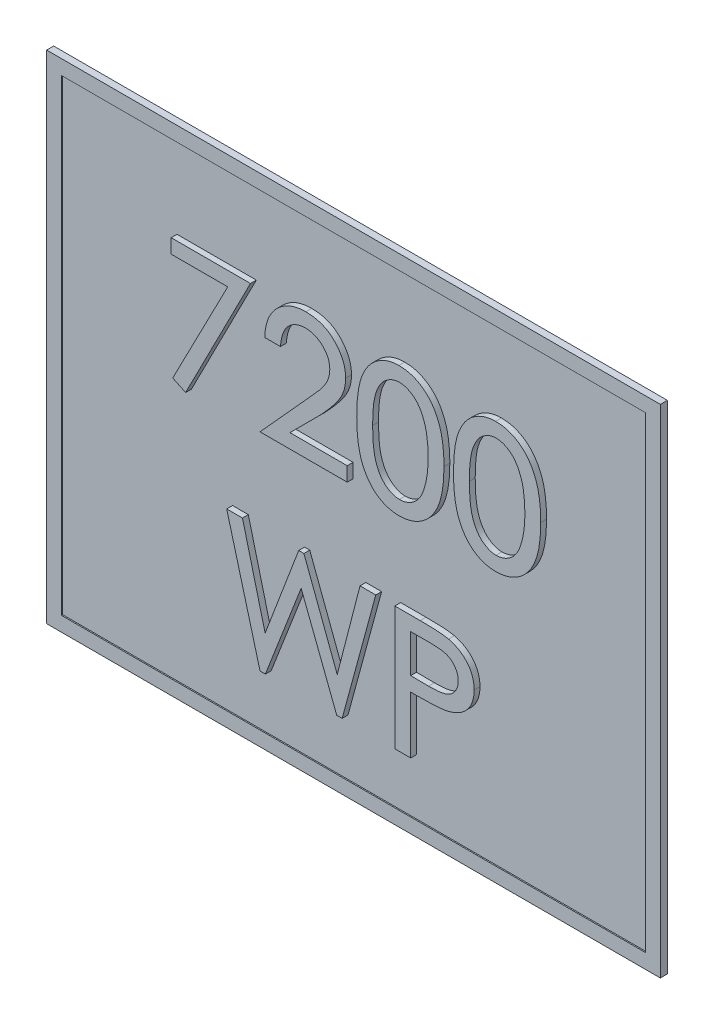
SolidWorks part; units mm, degrees
ref_plane "Front Plane" through (0, 0, 0) normal (0, 0, 1) x (1, 0, 0)
ref_plane "Top Plane" through (0, 0, 0) normal (0, 1, 0) x (1, 0, 0)
ref_plane "Right Plane" through (0, 0, 0) normal (1, 0, 0) x (0, 0, -1)
sketch "Sketch1" plane through (0, 0, 0) normal (0, 0, 1) x (1, 0, 0)
  line L0 (-500, 0) -> (500, 0) construction
  line L1 (-500, 400) -> (500, 400)
  line L2 (-500, 400) -> (-500, -400)
  line L3 (-500, -400) -> (500, -400)
  line L4 (500, 400) -> (500, -400)
  line L5 (-500, 400) -> (500, -400) construction
  line L6 (-500, -400) -> (500, 400) construction
  point P0 (0, 0)
  dimension "D1" = 1000
  dimension "D2" = 800
extrude "Boss-Extrude1" add sketch "Sketch1" along normal blind 10
sketch "Sketch2" plane through (0, 0, 10) normal (0, 0, 1) x (1, 0, 0)
  line L0 (-500, 49.8298) -> (500, 49.8298) construction
  line L3 (-500, 400) -> (-500, -400) construction
  line L4 (500, -400) -> (500, 400) construction
  line L5 (-500, -304.5438) -> (500, -304.5438) construction
  text T0 "<b>7200</b>" font "Century Gothic" height in points 800
  text T1 "<b>WP</b>" font "Century Gothic" height in points 800
extrude "Boss-Extrude2" add sketch "Sketch2" along normal blind 10
sketch "Sketch3" plane through (0, 0, 0) normal (0, 0, 1) x (1, 0, 0)
  line L1 (-500, -400) -> (500, -400)
  line L2 (-500, -400) -> (-500, 400)
  line L3 (-500, 400) -> (500, 400)
  line L4 (500, -400) -> (500, 400)
  line L5 (-500, -400) -> (500, 400) construction
  line L6 (-500, 400) -> (500, -400) construction
  line L7 (-525, -425) -> (525, -425)
  line L8 (-525, -425) -> (-525, 425)
  line L9 (-525, 425) -> (525, 425)
  line L10 (525, -425) -> (525, 425)
  line L11 (-525, -425) -> (525, 425) construction
  line L12 (-525, 425) -> (525, -425) construction
  point P0 (0, 0)
  point P7 (0, 0)
  dimension "D1" = 1050
  dimension "D2" = 850
extrude "Boss-Extrude3" add sketch "Sketch3" along normal blind 12
